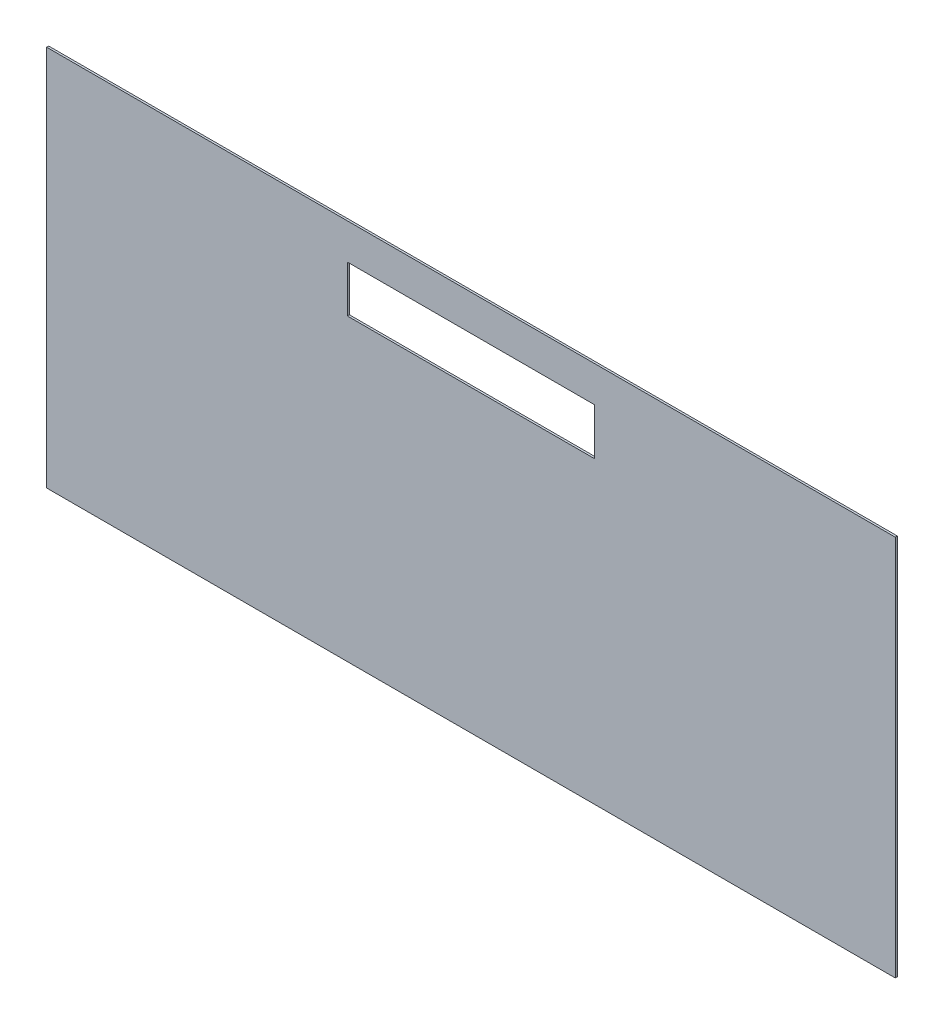
SolidWorks part; units mm, degrees
ref_plane "Front Plane" through (0, 0, 0) normal (0, 0, 1) x (1, 0, 0)
ref_plane "Top Plane" through (0, 0, 0) normal (0, 1, 0) x (1, 0, 0)
ref_plane "Right Plane" through (0, 0, 0) normal (1, 0, 0) x (0, 0, -1)
other "Configuration Table"
sketch "Sketch1" plane through (0, 0, 0) normal (0, 0, 1) x (1, 0, 0)
  line L1 (69, 406) -> (687, 406)
  line L2 (69, 406) -> (69, 684)
  line L3 (69, 684) -> (687, 684)
  line L4 (687, 406) -> (687, 684)
extrude "STORE_klape_kaset_kati_on_dis_sac_1" add sketch "Sketch1" along normal blind 1.5 from offset 38.5 separate body
sketch "Sketch2" plane through (0, 0, 0) normal (0, 0, 1) x (1, 0, 0)
  line L1 (288, 624) -> (468, 624)
  line L2 (288, 624) -> (288, 658)
  line L3 (288, 658) -> (468, 658)
  line L4 (468, 624) -> (468, 658)
extrude "STORE_klape_kaset_kati_on_dis_sac_2" cut sketch "Sketch2" along normal blind 14 from offset 27
